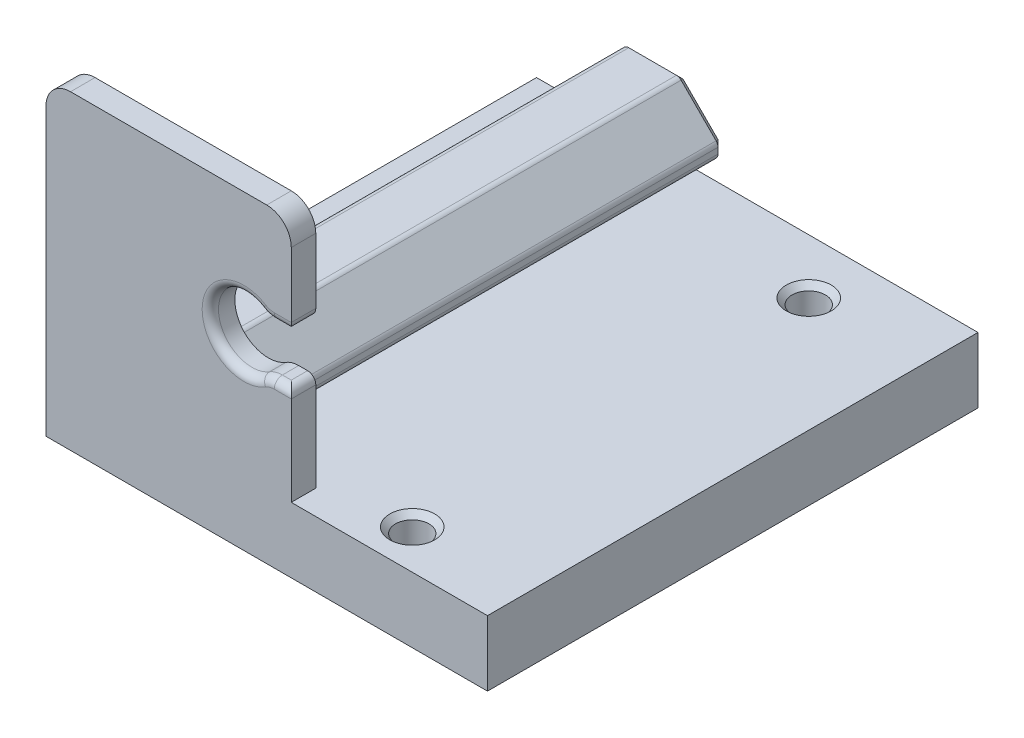
SolidWorks part; units mm, degrees
ref_plane "Front" through (0, 0, 0) normal (0, 0, 1) x (1, 0, 0)
ref_plane "Top" through (0, 0, 0) normal (0, 1, 0) x (1, 0, 0)
ref_plane "Right" through (0, 0, 0) normal (1, 0, 0) x (0, 0, -1)
sketch "Sketch1" plane through (0, 0, 0) normal (0, 0, 1) x (1, 0, 0)
  line L0 (54, 0) -> (54, 8)
  line L1 (0, 0) -> (54, 0)
  line L2 (0, 0) -> (0, 38)
  line L3 (0, 38) -> (30, 38)
  line L5 (54, 8) -> (30, 8)
  line L6 (30, 8) -> (30, 38)
  dimension "D1" = 38
  dimension "D2" = 30
  dimension "D3" = 54
  dimension "D4" = 8
extrude "Boss-Extrude1" add sketch "Sketch1" along normal blind 3
sketch "Sketch2" plane through (0, 0, 0) normal (0, 0, -1) x (-1, 0, 0)
  line L0 (0, 38) -> (0, 0) construction
  line L1 (-54, 0) -> (0, 0)
  line L2 (-54, 0) -> (-54, 8)
  line L3 (-54, 8) -> (0, 8)
  line L4 (0, 0) -> (0, 8)
  dimension "D1" = 8
extrude "Boss-Extrude2" add sketch "Sketch2" along normal blind 57
sketch "Sketch3" plane through (0, 0, 0) normal (0, -1, 0) x (1, 0, 0)
  line L0 (40, -1.8) -> (40, -50.3) construction
  line L1 (0, 3) -> (0, -57) construction
  line L2 (0, 3) -> (54, 3) construction
  circle A0 centre (40, -1.8) radius 2.05
  circle A1 centre (40, -50.3) radius 2.05
  dimension "D4" = 4.1
  dimension "D5" = 4.1
  dimension "D1" = 40
  dimension "D2" = 48.5
  dimension "D3" = 4.8
extrude "Cut-Extrude1" cut sketch "Sketch3" against normal blind 57
sketch "Sketch4" plane through (0, 0, 0) normal (0, 0, -1) x (-1, 0, 0)
  line L0 (-18, 8) -> (-18, 11)
  line L1 (0, 8) -> (-54, 8) construction
  line L2 (-18, 11) -> (-23, 11)
  line L3 (-23, 11) -> (-23, 12.85)
  line L4 (-23, 12.85) -> (-18.25, 17.6)
  line L5 (-18.25, 17.6) -> (-11.75, 17.6)
  line L6 (-11.75, 17.6) -> (-7, 12.85)
  line L7 (-7, 12.85) -> (-7, 11)
  line L8 (-7, 11) -> (-12, 11)
  line L9 (-12, 11) -> (-12, 8)
  line L10 (-12, 8) -> (-18, 8)
  line L11 (-15, 17.6) -> (-15, 8) construction
  line L12 (-15, 38) -> (-15, 8) construction
  line L13 (-30, 38) -> (0, 38) construction
  line L14 (0, 8) -> (-30, 8) construction
  dimension "D1" = 3
  dimension "D2" = 9.6
  dimension "D3" = 45
  dimension "D4" = 45
  dimension "D5" = 6.5
  dimension "D6" = 16
  dimension "D7" = 6
extrude "Boss-Extrude3" add sketch "Sketch4" along normal blind 57
fillet "Fillet1" radius 3 2 edges at (0, 38, 1.5) (30, 38, 1.5)
sketch "Sketch5" plane through (0, 0, 3) normal (0, 0, 1) x (1, 0, 0)
  line L0 (30, 26.05) -> (27.1, 26.05) construction
  line L1 (30, 8) -> (30, 35) construction
  line L2 (27.1, 26.05) -> (27.1, 31.1) construction
  line L3 (27.1, 31.1) -> (24.95, 31.1) construction
  line L4 (24.95, 31.1) -> (20.1, 26.25) construction
  line L5 (20.1, 26.25) -> (20.1, 19.75) construction
  line L6 (20.1, 19.75) -> (24.95, 14.9) construction
  line L7 (24.95, 14.9) -> (27.1, 14.9) construction
  line L8 (27.1, 14.9) -> (27.1, 19.95) construction
  line L9 (27.1, 19.95) -> (30, 19.95) construction
  line L10 (30, 19.95) -> (30, 26.05) construction
  line L11 (20.1, 23) -> (30, 23) construction
  line L12 (27, 38) -> (3, 38) construction
  line L13 (27.9158, 26.05) -> (30, 26.05)
  line L14 (30, 26.05) -> (30, 19.95)
  line L15 (30, 19.95) -> (27.9158, 19.95)
  circle A0 centre (24.2, 23) radius 4.1 construction
  arc A1 (26.3458, 19.5063) -> (26.3458, 26.4937) centre (24.2, 23) cw
  arc A2 (26.3458, 19.5063) -> (27.9158, 19.95) centre (27.9158, 16.95) cw
  arc A3 (26.3458, 26.4937) -> (27.9158, 26.05) centre (27.9158, 29.05) ccw
  point P21 (26.94, 19.95)
  point P23 (26.94, 19.95)
  point P26 (26.94, 26.05)
  dimension "D9" = 8.2
  dimension "D10" = 3
  dimension "D1" = 45
  dimension "D2" = 45
  dimension "D3" = 6.5
  dimension "D4" = 6.1
  dimension "D5" = 2.9
  dimension "D6" = 9.9
  dimension "D7" = 16.2
  dimension "D8" = 15
extrude "Cut-Extrude2" cut sketch "Sketch5" against normal blind 6
fillet "Fillet2" radius 1 7 edges at (28.9579, 26.05, 3) (27.1001, 26.163, 3) (28.9579, 19.95, 3) (27.1001, 19.837, 3) (20.1, 23, 3) (30, 19.95, 1.5) (30, 26.05, 1.5)
fillet "Fillet3" radius 0.8 6 edges at (23, 11, -28.5) (7, 11, -28.5) (7, 12.85, -28.5) (11.75, 17.6, -28.5) (18.25, 17.6, -28.5) (23, 12.85, -28.5)
chamfer "Chamfer1" distance 0.8 angle 45 15 edges at (12, 9.5, -57) (18, 9.5, -57) (9.9, 11, -57) (7.2343, 11.2343, -57) (7, 12.1593, -57) (7.0609, 12.8248, -57) (9.375, 15.225, -57) (20.1, 11, -57) (11.7752, 17.5391, -57) (22.7657, 11.2343, -57) (15, 17.6, -57) (23, 12.1593, -57) (18.2248, 17.5391, -57) (22.9391, 12.8248, -57) (20.625, 15.225, -57)
chamfer "Chamfer2" distance 0.7 angle 45 4 edges at (42.05, 8, -50.3) (40, 0, -52.35) (42.05, 8, -1.8) (40, 0, -3.85)
